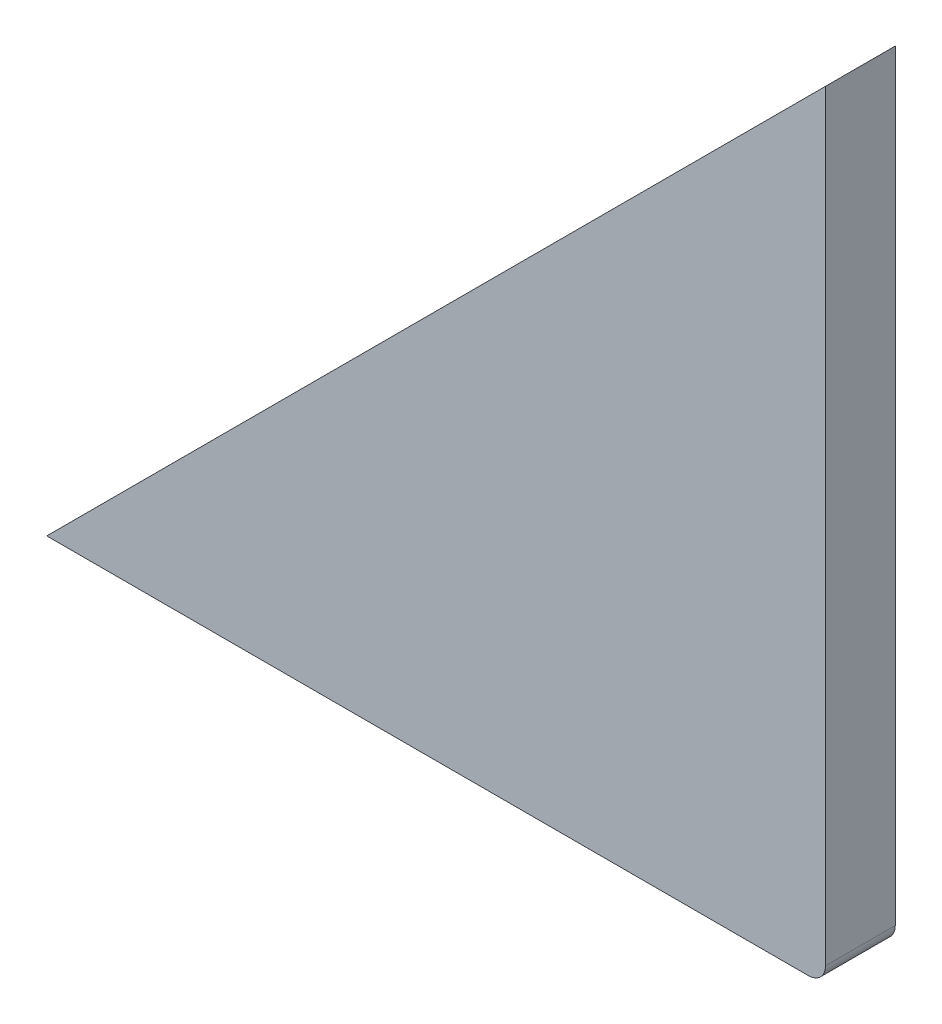
SolidWorks part; units mm, degrees
ref_plane "Front Plane" through (0, 0, 0) normal (0, 0, 1) x (1, 0, 0)
ref_plane "Top Plane" through (0, 0, 0) normal (0, 1, 0) x (1, 0, 0)
ref_plane "Right Plane" through (0, 0, 0) normal (1, 0, 0) x (0, 0, -1)
sketch "Sketch1" plane through (0, 0, 8.8334) normal (0, 0, 1) x (1, 0, 0)
  line L0 (-114, 13.6009) -> (-81.2366, 13.6009)
  line L1 (-114, 13.6009) -> (-81.2366, 13.6009)
  line L2 (-80.5, 47.1009) -> (-80.5, 14.3375)
  line L3 (-80.5, 47.1009) -> (-80.5, 14.3375)
  line L4 (-80.5, 47.1009) -> (-114, 13.6009)
  arc A0 (-81.2366, 13.6009) -> (-80.5, 14.3375) centre (-81.2366, 14.3375) ccw
  arc A1 (-81.2366, 13.6009) -> (-80.5, 14.3375) centre (-81.2366, 14.3375) ccw
extrude "Boss-Extrude1" add sketch "Sketch1" along normal mid plane 3
